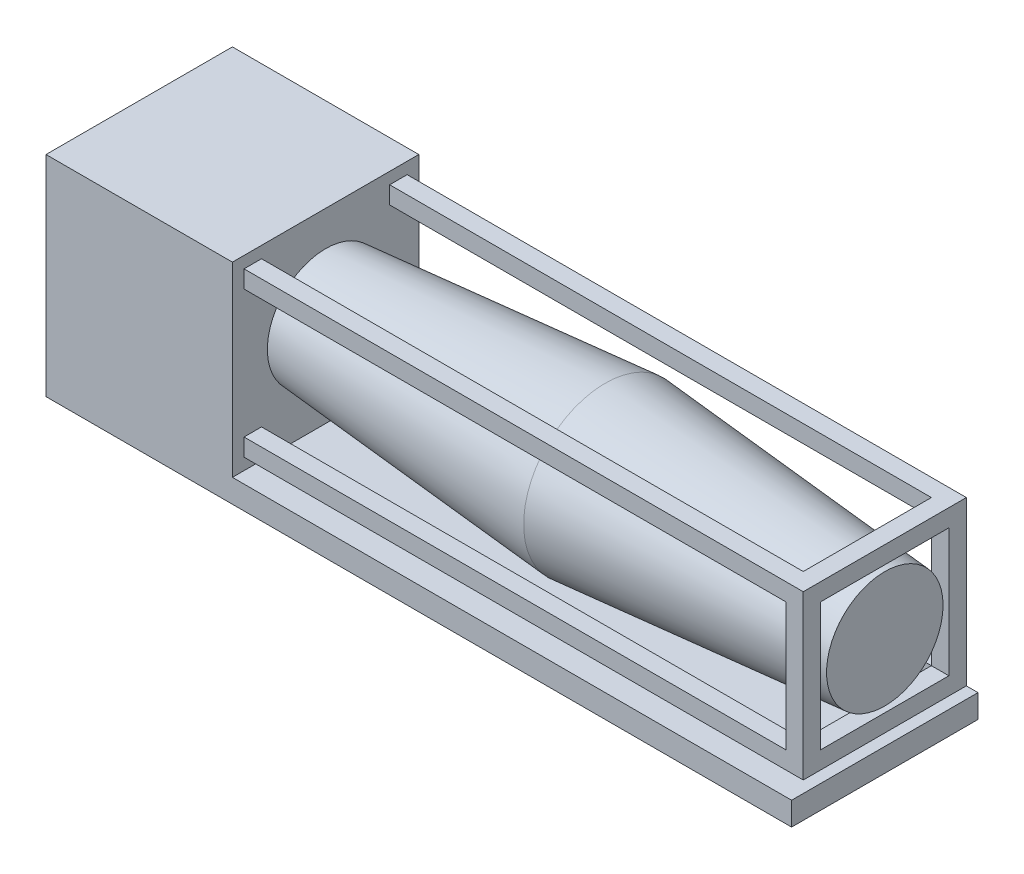
SolidWorks part; units mm, degrees
ref_plane "Front Plane" through (0, 0, 0) normal (0, 0, 1) x (1, 0, 0)
ref_plane "Top Plane" through (0, 0, 0) normal (0, 1, 0) x (1, 0, 0)
ref_plane "Right Plane" through (0, 0, 0) normal (1, 0, 0) x (0, 0, -1)
sketch "Sketch1" plane through (0, 0, 0) normal (0, 1, 0) x (1, 0, 0)
  line L1 (0, 0) -> (640, 0)
  line L2 (0, 0) -> (0, 160)
  line L3 (0, 160) -> (640, 160)
  line L4 (640, 0) -> (640, 160)
  dimension "D1" = 160
  dimension "D2" = 640
extrude "Boss-Extrude1" add sketch "Sketch1" along normal blind 180
sketch "Sketch2" plane through (640, 0, 0) normal (1, 0, 0) x (0, 0, -1)
  line L0 (160, 180) -> (160, 0) construction
  line L1 (0, 180) -> (160, 180)
  line L2 (0, 180) -> (0, 20)
  line L3 (0, 20) -> (160, 20)
  line L4 (160, 180) -> (160, 20)
  dimension "D1" = 160
extrude "Cut-Extrude1" cut sketch "Sketch2" against normal blind 480
sketch "Sketch3" plane through (160, 0, 0) normal (1, 0, 0) x (0, 0, -1)
  line L0 (0, 100) -> (160, 100) construction
  line L1 (0, 180) -> (0, 20) construction
  line L2 (160, 20) -> (160, 180) construction
  circle A0 centre (80, 100) radius 70
  dimension "D1" = 140
extrude "Boss-Extrude2" add sketch "Sketch3" along normal up to surface (480 mm away) up to face at (640, 10, -80)
ref_plane "Plane1" through (0, 0, -80) normal (0, 0, 1) x (1, 0, 0)
ref_plane "Plane2" through (0, 100, 0) normal (0, 1, 0) x (1, 0, 0)
sketch "Sketch6" plane through (0, 0, -80) normal (0, 0, 1) x (1, 0, 0)
  line L0 (640, 100) -> (160, 100) construction
  line L1 (640, 30) -> (640, 170) construction
  line L2 (160, 180) -> (160, 20) construction
  line L3 (400, 100) -> (400, 170) construction
  line L4 (640, 170) -> (160, 170) construction
  line L5 (400, 170) -> (640, 170)
  line L6 (640, 170) -> (640, 150)
  line L7 (640, 150) -> (400, 170)
  line L8 (400, 170) -> (160, 170)
  line L9 (160, 170) -> (160, 150)
  line L10 (160, 30) -> (160, 170) construction
  line L11 (160, 150) -> (400, 170)
  dimension "D1" = 20
revolve "Cut-Revolve1" cut sketch "Sketch6" angle 360 about L0
sketch "Sketch4" plane through (160, 0, 0) normal (1, 0, 0) x (0, 0, -1)
  line L0 (0, 180) -> (10, 180) construction
  line L1 (160, 180) -> (0, 180) construction
  line L2 (0, 180) -> (0, 170) construction
  line L3 (0, 180) -> (0, 20) construction
  line L4 (0, 170) -> (10, 170) construction
  line L5 (10, 170) -> (10, 180) construction
  line L6 (80, 180) -> (80, 20) construction
  line L7 (10, 170) -> (25, 170)
  line L8 (10, 170) -> (10, 155)
  line L9 (10, 155) -> (25, 155)
  line L10 (25, 170) -> (25, 155)
  line L11 (0, 20) -> (160, 20) construction
  line L12 (0, 100) -> (160, 100) construction
  line L13 (160, 20) -> (160, 180) construction
  line L14 (150, 155) -> (135, 155)
  line L15 (135, 170) -> (135, 155)
  line L16 (150, 170) -> (135, 170)
  line L17 (150, 170) -> (150, 155)
  line L18 (150, 30) -> (150, 45)
  line L19 (150, 30) -> (135, 30)
  line L20 (135, 30) -> (135, 45)
  line L21 (150, 45) -> (135, 45)
  line L22 (10, 45) -> (25, 45)
  line L23 (25, 30) -> (25, 45)
  line L24 (10, 30) -> (25, 30)
  line L25 (10, 30) -> (10, 45)
  dimension "D1" = 10
  dimension "D2" = 15
extrude "Boss-Extrude3" add sketch "Sketch4" along normal up to surface (480 mm away) up to face at (640, 10, -80)
sketch "Sketch7" plane through (0, 0, -25) normal (0, 0, -1) x (-1, 0, 0)
  line L0 (-640, 155) -> (-160, 155) construction
  line L1 (-640, 170) -> (-625, 170)
  line L2 (-640, 170) -> (-640, 155)
  line L3 (-640, 155) -> (-625, 155)
  line L4 (-625, 170) -> (-625, 155)
  dimension "D1" = 15
extrude "Boss-Extrude4" add sketch "Sketch7" along normal up to surface (110 mm away) up to face at (400, 162.5, -135)
mirror "Mirror1" about plane through (0, 100, 0) normal (0, 1, 0) of "Boss-Extrude4"
sketch "Sketch8" plane through (0, 45, 0) normal (0, 1, 0) x (1, 0, 0)
  line L1 (640, 10) -> (625, 10)
  line L2 (640, 10) -> (640, 25)
  line L3 (640, 25) -> (625, 25)
  line L4 (625, 10) -> (625, 25)
  line L5 (625, 135) -> (640, 135)
  line L6 (625, 135) -> (625, 150)
  line L7 (625, 150) -> (640, 150)
  line L8 (640, 135) -> (640, 150)
extrude "Boss-Extrude5" add sketch "Sketch8" along normal up to surface (110 mm away) up to face at (396.25, 155, -80)
